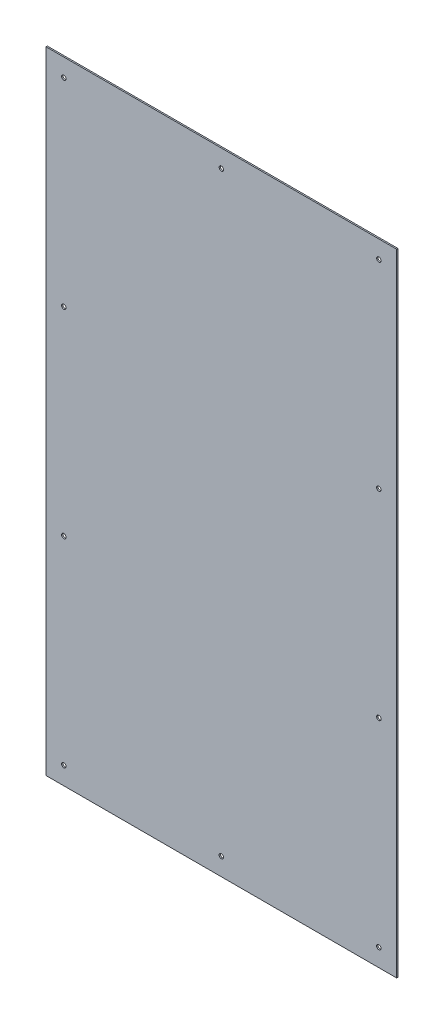
SolidWorks part; units mm, degrees
ref_plane "Alzado" through (0, 0, 0) normal (0, 0, 1) x (1, 0, 0)
ref_plane "Planta" through (0, 0, 0) normal (0, 1, 0) x (1, 0, 0)
ref_plane "Vista lateral" through (0, 0, 0) normal (1, 0, 0) x (0, 0, -1)
sketch "Croquis1" plane through (0, 0, 0) normal (0, 0, 1) x (1, 0, 0)
  line L1 (-250, 450) -> (250, 450)
  line L2 (-250, 450) -> (-250, -450)
  line L3 (-250, -450) -> (250, -450)
  line L4 (250, 450) -> (250, -450)
  line L5 (-250, 450) -> (250, -450) construction
  line L6 (-250, -450) -> (250, 450) construction
  point P0 (0, 0)
  dimension "D1" = 500
  dimension "D2" = 900
extrude "Saliente-Extruir1" add sketch "Croquis1" along normal blind 1.9
sketch "Croquis2" plane through (0, 0, 1.9) normal (0, 0, 1) x (1, 0, 0)
  line L0 (250, 450) -> (-250, 450) construction
  line L1 (-224.6, -424.6) -> (224.6, -424.6) construction
  line L2 (-224.6, -424.6) -> (-224.6, 424.6) construction
  line L3 (-224.6, 424.6) -> (224.6, 424.6) construction
  line L4 (224.6, -424.6) -> (224.6, 424.6) construction
  line L5 (-224.6, -424.6) -> (224.6, 424.6) construction
  line L6 (-224.6, 424.6) -> (224.6, -424.6) construction
  line L7 (250, -450) -> (250, 450) construction
  line L8 (0, 0) -> (0, 424.6) construction
  line L9 (-224.6, 0) -> (224.6, 0) construction
  circle A0 centre (-224.6, 424.6) radius 3.175
  circle A1 centre (224.6, 424.6) radius 3.175
  circle A2 centre (224.6, -424.6) radius 3.175
  circle A3 centre (-224.6, -424.6) radius 3.175
  circle A4 centre (-224.6, 141.54) radius 3.175
  circle A5 centre (-224.6, -141.52) radius 3.175
  circle A6 centre (224.6, -141.52) radius 3.175
  circle A7 centre (224.6, 141.54) radius 3.175
  circle A8 centre (0, 424.6) radius 3.175
  circle A9 centre (0, -424.6) radius 3.175
  point P0 (0, 0)
  dimension "D3" = 6.35
  dimension "D5" = 6.35
  dimension "D1" = 25.4
  dimension "D2" = 25.4
  dimension "D4" = 3
extrude "Cortar-Extruir1" cut sketch "Croquis2" against normal blind 10
